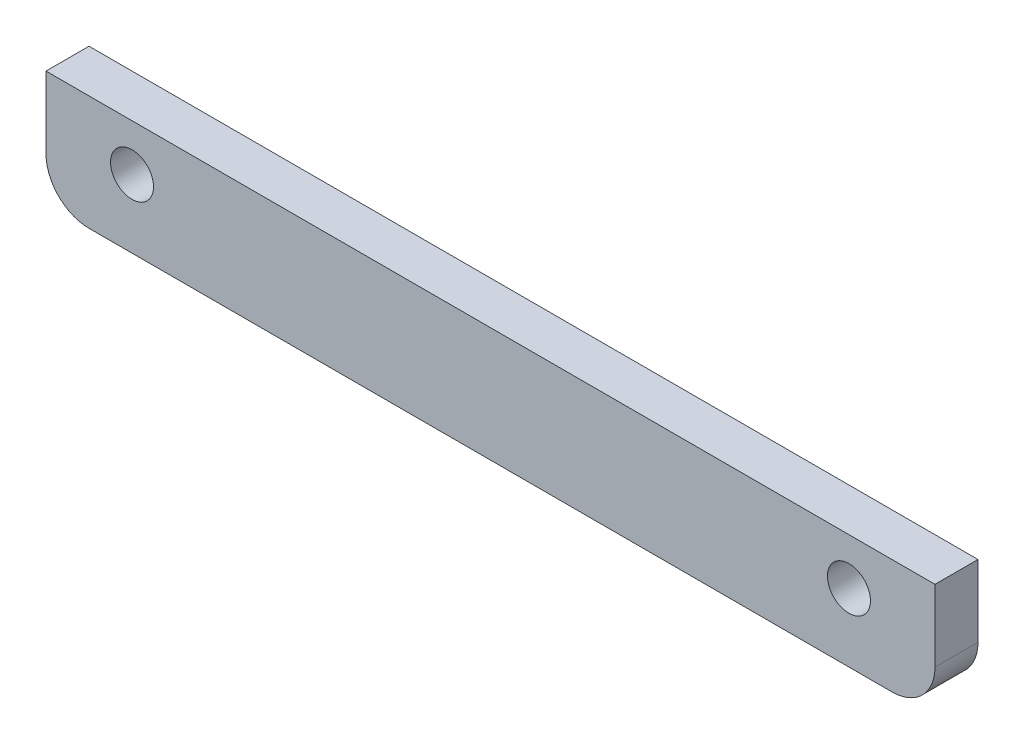
SolidWorks part; units mm, degrees
ref_plane "Front Plane" through (0, 0, 0) normal (0, 0, 1) x (1, 0, 0)
ref_plane "Top Plane" through (0, 0, 0) normal (0, 1, 0) x (1, 0, 0)
ref_plane "Right Plane" through (0, 0, 0) normal (1, 0, 0) x (0, 0, -1)
sketch "Sketch1" plane through (0, 0, 0) normal (0, 0, 1) x (1, 0, 0)
  line L1 (-31, 2.5) -> (31, 2.5)
  line L2 (-31, 2.5) -> (-31, -2.5)
  line L3 (-28, -5.5) -> (28, -5.5)
  line L4 (31, 2.5) -> (31, -2.5)
  line L5 (0, -5.5) -> (0, 2.5) construction
  line L6 (-31, 0) -> (31, 0) construction
  arc A0 (28, -5.5) -> (31, -2.5) centre (28, -2.5) ccw
  arc A1 (-31, -2.5) -> (-28, -5.5) centre (-28, -2.5) ccw
  circle A2 centre (-25, -0.75) radius 1.5
  circle A3 centre (25, -0.75) radius 1.5
  point P0 (0, 0)
  point P6 (31, -5.5)
  point P9 (-31, -5.5)
  dimension "D3" = 3
  dimension "D1" = 62
  dimension "D2" = 8
extrude "Boss-Extrude1" add sketch "Sketch1" along normal blind 3
